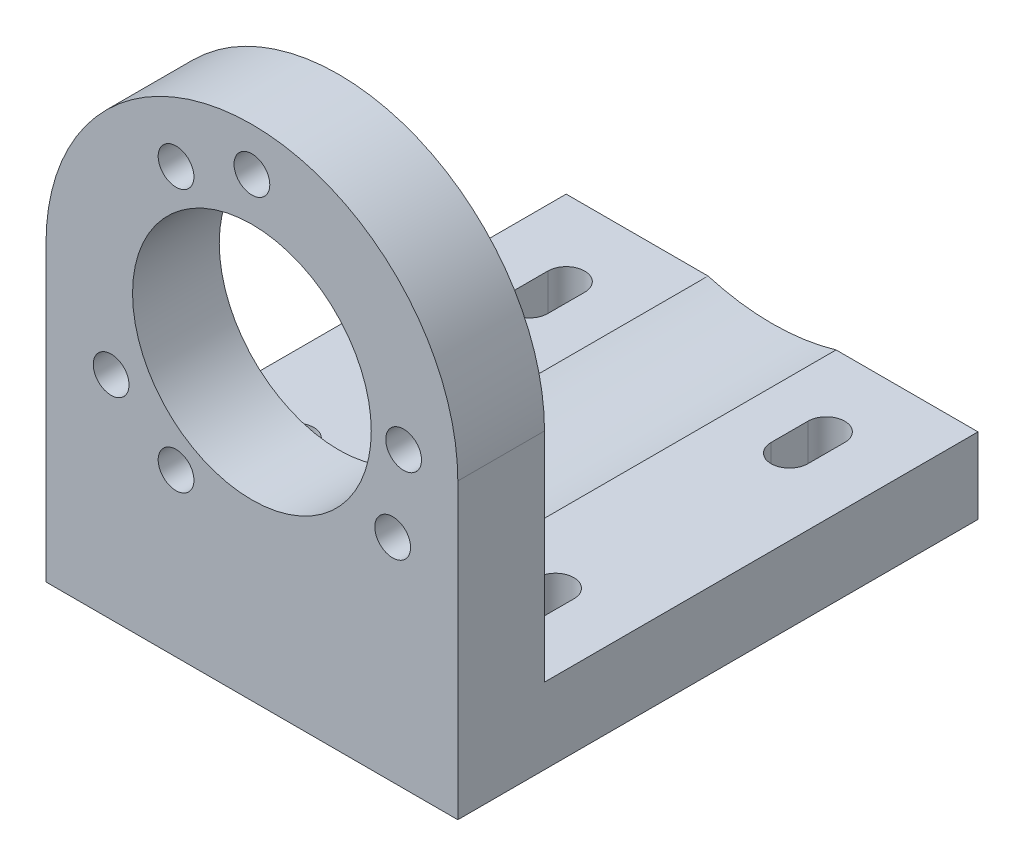
SolidWorks part; units mm, degrees
ref_plane "Front Plane" through (0, 0, 0) normal (0, 0, 1) x (1, 0, 0)
ref_plane "Top Plane" through (0, 0, 0) normal (0, 1, 0) x (1, 0, 0)
ref_plane "Right Plane" through (0, 0, 0) normal (1, 0, 0) x (0, 0, -1)
sketch "Sketch1" plane through (0, 0, 0) normal (0, 0, 1) x (1, 0, 0)
  line L3 (0, -22.0729) -> (-19, -22.0729)
  line L4 (-19, 0) -> (-19, -22.0729)
  line L7 (0, -22.0729) -> (19, -22.0729)
  line L8 (19, 0) -> (19, -22.0729)
  arc A15 (-11.3404, -7.5) -> (-14.6404, -7.5) centre (-12.9904, -7.5) ccw
  arc A16 (-14.6404, -7.5) -> (-11.3404, -7.5) centre (-12.9904, -7.5) ccw
  arc A17 (-5.35, -12.1244) -> (-8.65, -12.1244) centre (-7, -12.1244) ccw
  arc A18 (-8.65, -12.1244) -> (-5.35, -12.1244) centre (-7, -12.1244) ccw
  arc A19 (11.3404, -7.5) -> (14.6404, -7.5) centre (12.9904, -7.5) ccw
  arc A20 (14.6404, -7.5) -> (11.3404, -7.5) centre (12.9904, -7.5) ccw
  arc A21 (15.65, 0) -> (12.35, 0) centre (14, 0) ccw
  arc A22 (12.35, 0) -> (15.65, 0) centre (14, 0) ccw
  arc A23 (-1.65, 15) -> (1.65, 15) centre (0, 15) ccw
  arc A24 (1.65, 15) -> (-1.65, 15) centre (0, 15) ccw
  arc A25 (-5.35, 12.1244) -> (-8.65, 12.1244) centre (-7, 12.1244) ccw
  arc A26 (-8.65, 12.1244) -> (-5.35, 12.1244) centre (-7, 12.1244) ccw
  arc A29 (19, 0) -> (-19, 0) centre (0, 0) ccw
  circle A32 centre (0, 0) radius 11.0139
extrude "Boss-Extrude1" add sketch "Sketch1" along normal blind 8
sketch "Sketch2" plane through (0, -22.0729, 0) normal (0, -1, 0) x (1, 0, 0)
  line L1 (19, 8) -> (-19, 8)
  line L2 (19, 8) -> (19, -40)
  line L3 (19, -40) -> (-19, -40)
  line L4 (-19, 8) -> (-19, -40)
extrude "Boss-Extrude2" add sketch "Sketch2" along normal blind 5 and the other way blind 2
sketch "Sketch3" plane through (0, 0, 0) normal (0, 0, -1) x (-1, 0, 0)
  line L0 (5.9044, -20.0729) -> (-5.9044, -20.0729)
  line L1 (19, -20.0729) -> (-19, -20.0729) construction
  arc A0 (-5.9044, -20.0729) -> (5.9044, -20.0729) centre (0, 0) ccw
extrude "Cut-Extrude1" cut sketch "Sketch3" along normal blind 51
sketch "Sketch4" plane through (0, -20.0729, 0) normal (0, 1, 0) x (1, 0, 0)
  line L3 (-13.7, 8.0064) -> (-13.7, 4.6064)
  line L4 (-10.3, 8.0064) -> (-10.3, 4.6064)
  line L5 (-13.7, 33.0064) -> (-13.7, 29.6064)
  line L6 (-10.3, 33.0064) -> (-10.3, 29.6064)
  line L7 (13.7, 33.0064) -> (13.7, 29.6064)
  line L8 (10.3, 33.0064) -> (10.3, 29.6064)
  line L9 (13.7, 8.0064) -> (13.7, 4.6064)
  line L10 (10.3, 8.0064) -> (10.3, 4.6064)
  arc A4 (-13.7, 29.6064) -> (-10.3, 29.6064) centre (-12, 29.6064) ccw
  arc A5 (-10.3, 33.0064) -> (-13.7, 33.0064) centre (-12, 33.0064) ccw
  arc A6 (13.7, 33.0064) -> (10.3, 33.0064) centre (12, 33.0064) ccw
  arc A7 (10.3, 29.6064) -> (13.7, 29.6064) centre (12, 29.6064) ccw
  arc A8 (13.7, 8.0064) -> (10.3, 8.0064) centre (12, 8.0064) ccw
  arc A9 (10.3, 4.6064) -> (13.7, 4.6064) centre (12, 4.6064) ccw
  arc A10 (-10.3, 8.0064) -> (-13.7, 8.0064) centre (-12, 8.0064) ccw
  arc A12 (-13.7, 4.6064) -> (-10.3, 4.6064) centre (-12, 4.6064) ccw
extrude "Cut-Extrude2" cut sketch "Sketch4" against normal blind 51
